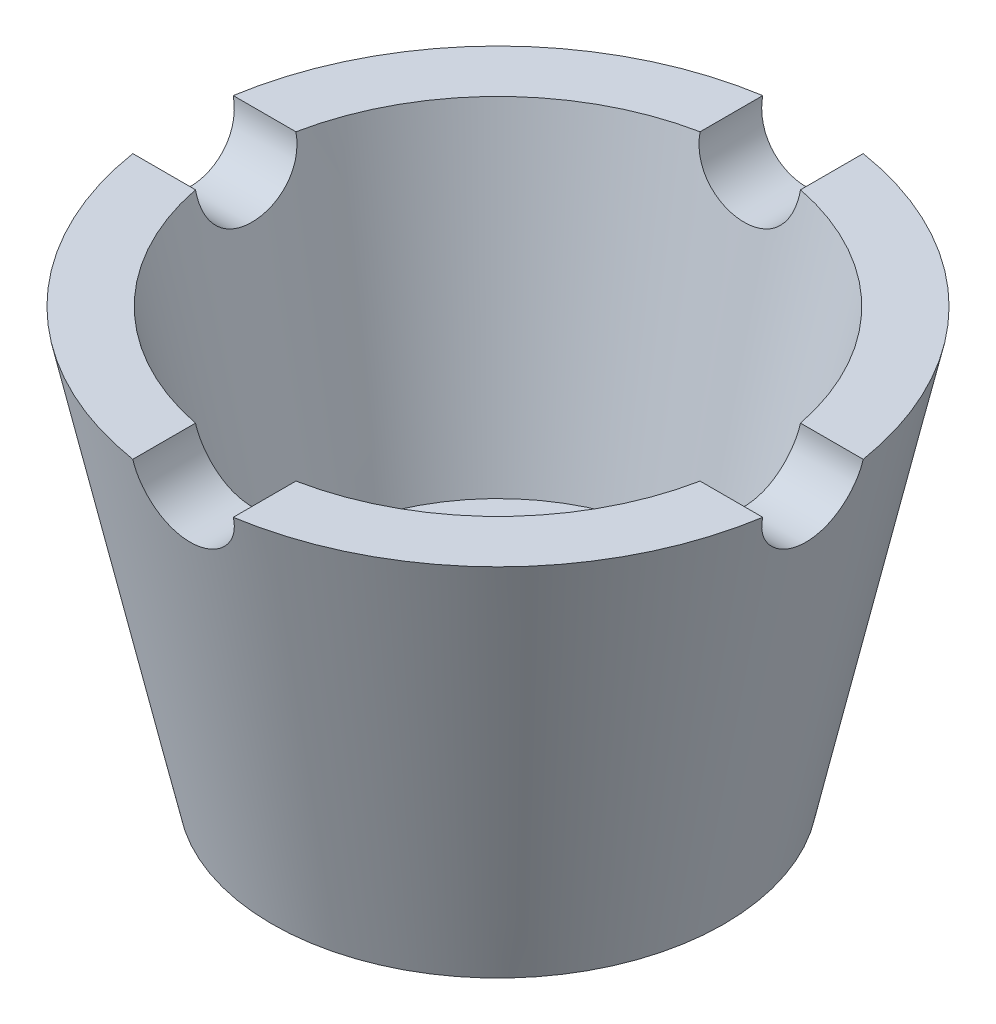
SolidWorks part; units mm, degrees
material "AISI 1020"
ref_plane "Front Plane" through (0, 0, 0) normal (0, 0, 1) x (1, 0, 0)
ref_plane "Top Plane" through (0, 0, 0) normal (0, 1, 0) x (1, 0, 0)
ref_plane "Right Plane" through (0, 0, 0) normal (1, 0, 0) x (0, 0, -1)
sketch "Sketch1" plane through (0, 0, 0) normal (0, 0, 1) x (1, 0, 0)
  line L0 (11, 0) -> (11, 12)
  line L1 (11, 12) -> (19, 12)
  line L2 (19, 12) -> (25.6098, 42)
  line L3 (25.6098, 42) -> (31.7537, 42)
  line L4 (31.7537, 42) -> (22.5, 0)
  line L5 (22.5, 0) -> (11, 0)
  line L6 (0, 0) -> (0, 42) construction
  point P2 (11, 6)
  point P10 (0, 0)
  dimension "D1" = 22.5
  dimension "11" = 11
  dimension "D2" = 42
  dimension "D3" = 12
  dimension "D4" = 19
  dimension "D5" = 6
revolve "Revolve1" add sketch "Sketch1" angle 360 about L6
sketch "Sketch2" plane through (0, 0, 0) normal (0, 0, 1) x (1, 0, 0)
  line L0 (31.7537, 42) -> (-31.7537, 42) construction
  circle A0 centre (0, 42) radius 5
  dimension "D1" = 10
extrude "Cut-Extrude1" cut sketch "Sketch2" against normal blind 50
pattern_circular "CirPattern1" count 4 over 360 about axis through (0, 0, 0) along (0, 1, 0) of "Cut-Extrude1"
